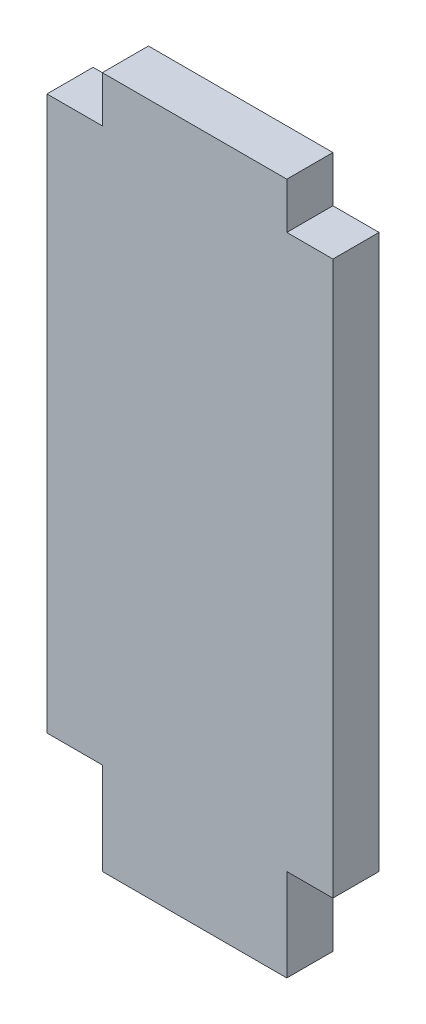
SolidWorks part; units mm, degrees
material "Beech"
ref_plane "Front" through (0, 0, 0) normal (0, 0, 1) x (1, 0, 0)
ref_plane "Top" through (0, 0, 0) normal (0, 1, 0) x (1, 0, 0)
ref_plane "Right" through (0, 0, 0) normal (1, 0, 0) x (0, 0, -1)
sketch "Sketch1" plane through (0, 0, 0) normal (0, 0, 1) x (1, 0, 0)
  line L0 (-7.75, 16.25) -> (-4.75, 16.25)
  line L1 (-7.75, -18.75) -> (7.75, -18.75) construction
  line L2 (-7.75, -18.75) -> (-7.75, 18.75) construction
  line L3 (-7.75, 18.75) -> (7.75, 18.75) construction
  line L4 (7.75, -18.75) -> (7.75, 18.75) construction
  line L5 (-7.75, -18.75) -> (7.75, 18.75) construction
  line L6 (-7.75, 18.75) -> (7.75, -18.75) construction
  line L7 (-4.75, 16.25) -> (-4.75, 18.75)
  line L8 (-4.75, 18.75) -> (5.25, 18.75)
  line L9 (5.25, 18.75) -> (5.25, 16.25)
  line L10 (5.25, 16.25) -> (7.75, 16.25)
  line L11 (7.75, 16.25) -> (7.75, -13.75)
  line L12 (7.75, -13.75) -> (5.25, -13.75)
  line L13 (5.25, -13.75) -> (5.25, -18.75)
  line L14 (5.25, -18.75) -> (-4.75, -18.75)
  line L15 (-4.75, -18.75) -> (-4.75, -13.75)
  line L16 (-4.75, -13.75) -> (-7.75, -13.75)
  line L17 (-7.75, -13.75) -> (-7.75, 16.25)
  point P0 (0, 0)
  dimension "D1" = 15.5
  dimension "D2" = 37.5
  dimension "D3" = 5
  dimension "D4" = 2.5
  dimension "D5" = 3
  dimension "D6" = 10
extrude "Boss-Extrude1" add sketch "Sketch1" along normal blind 2.5
